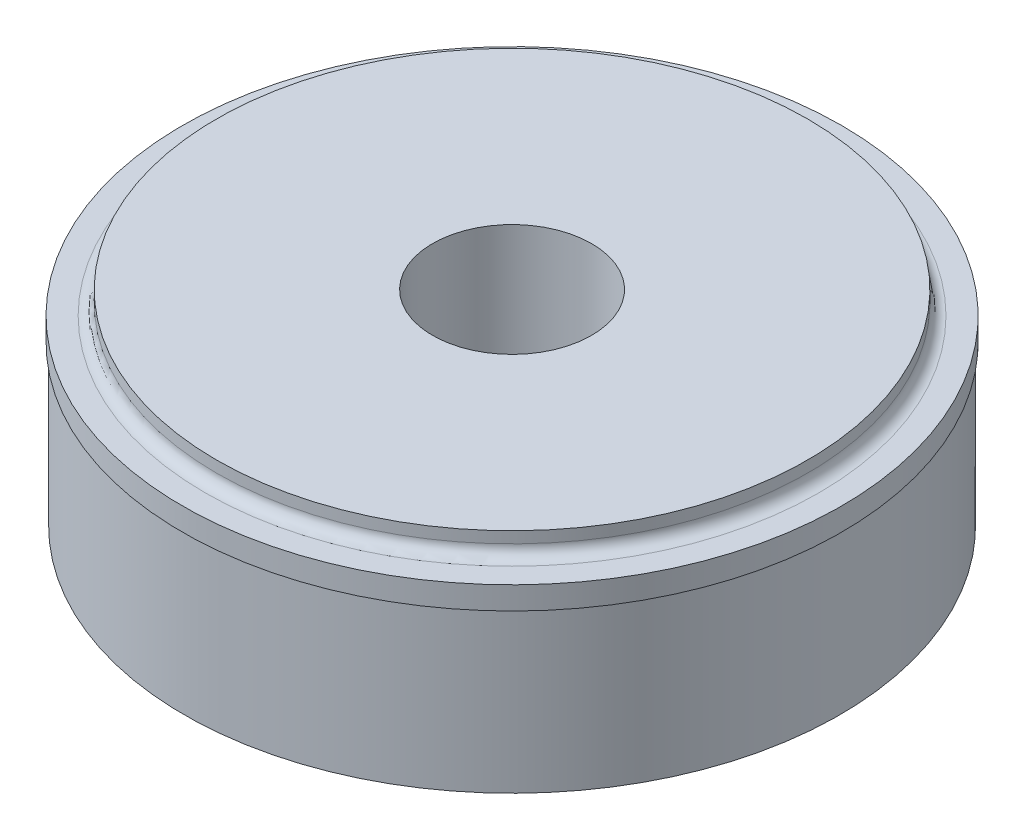
SolidWorks part; units mm, degrees
material "延性铁"
ref_plane "前视基准面" through (0, 0, 0) normal (0, 0, 1) x (1, 0, 0)
ref_plane "上视基准面" through (0, 0, 0) normal (0, 1, 0) x (1, 0, 0)
ref_plane "右视基准面" through (0, 0, 0) normal (1, 0, 0) x (0, 0, -1)
sketch "草图1" plane through (0, 0, 0) normal (1, 0, 0) x (0, 0, -1)
  line L0 (0, 0) -> (0, 38.8583) construction
  line L1 (-17.5, 45) -> (-17.5, 0)
  line L2 (-17.5, 0) -> (-72.1, 0)
  line L3 (-72.1, 0) -> (-72.1, 35)
  line L4 (-72.1, 35) -> (-72.5, 35)
  line L5 (-72.5, 35) -> (-72.5, 40)
  line L6 (-72.5, 40) -> (-67.5, 40)
  line L7 (-65, 42.5) -> (-65, 45)
  line L8 (-65, 45) -> (-17.5, 45)
  arc A0 (-67.5, 40) -> (-65, 42.5) centre (-67.5, 42.5) ccw
  point P13 (-65, 40)
  dimension "D8" = 2.5
  dimension "D1" = 35
  dimension "D2" = 145
  dimension "D3" = 144.2
  dimension "D4" = 130
  dimension "D5" = 5
  dimension "D6" = 5
  dimension "D7" = 45
revolve "旋转1" add sketch "草图1" angle 360 about L0
